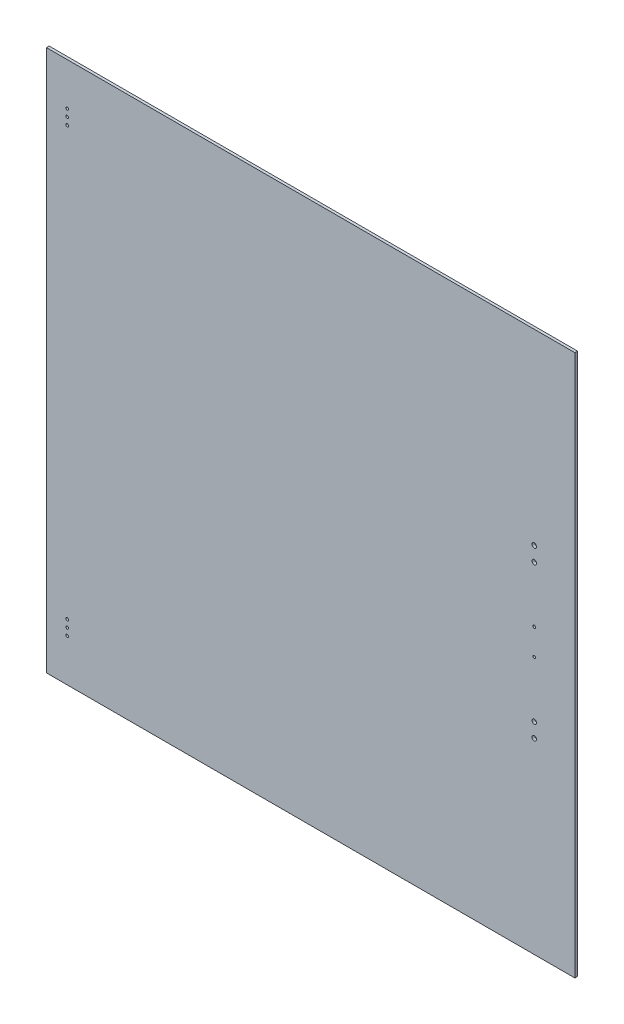
SolidWorks part; units mm, degrees
material "Acrylic (Medium-high impact)"
ref_plane "Front Plane" through (0, 0, 0) normal (0, 0, 1) x (1, 0, 0)
ref_plane "Top Plane" through (0, 0, 0) normal (0, 1, 0) x (1, 0, 0)
ref_plane "Right Plane" through (0, 0, 0) normal (1, 0, 0) x (0, 0, -1)
sketch "Sketch1" plane through (0, 0, 0) normal (0, 0, 1) x (1, 0, 0)
  line L1 (-476.5049, 294.7573) -> (108.9951, 294.7573)
  line L2 (-476.5049, 294.7573) -> (-476.5049, -305.2427)
  line L3 (-476.5049, -305.2427) -> (108.9951, -305.2427)
  line L4 (108.9951, 294.7573) -> (108.9951, -305.2427)
  dimension "D1" = 600
  dimension "D2" = 585.5
extrude "Boss-Extrude1" add sketch "Sketch1" along normal blind 3
sketch "Sketch2" plane through (0, 0, 3) normal (0, 0, 1) x (1, 0, 0)
  line L0 (-476.5049, 294.7573) -> (-476.5049, -305.2427) construction
  line L1 (108.9951, 294.7573) -> (-476.5049, 294.7573) construction
  line L2 (-476.5049, -305.2427) -> (108.9951, -305.2427) construction
  circle A0 centre (-453.5049, 247.7573) radius 1.5
  circle A1 centre (-453.5049, 239.7573) radius 1.5
  circle A2 centre (-453.5049, 231.7573) radius 1.5
  circle A3 centre (-453.5049, -242.2427) radius 1.5
  circle A4 centre (-453.5049, -250.2427) radius 1.5
  circle A5 centre (-453.5049, -258.2427) radius 1.5
  dimension "D1" = 3
  dimension "D4" = 8
  dimension "D5" = 23
  dimension "D6" = 8
  dimension "D7" = 23
  dimension "D8" = 3
  dimension "D11" = 47
  dimension "D12" = 23
  dimension "D2" = 23
  dimension "D3" = 47
  dimension "D9" = 8
  dimension "D10" = 8
extrude "Cut-Extrude1" cut sketch "Sketch2" against normal through all
sketch "Sketch3" plane through (0, 0, 3) normal (0, 0, 1) x (1, 0, 0)
  line L0 (-476.5049, -5.2427) -> (108.9951, -5.2427) construction
  line L1 (-476.5049, 294.7573) -> (-476.5049, -305.2427) construction
  line L2 (108.9951, -305.2427) -> (108.9951, 294.7573) construction
  line L3 (63.9951, 294.7573) -> (63.9951, -305.2427) construction
  line L4 (108.9951, 294.7573) -> (-476.5049, 294.7573) construction
  line L5 (-476.5049, -305.2427) -> (108.9951, -305.2427) construction
  circle A0 centre (63.9951, 87.2573) radius 2.5
  circle A1 centre (63.9951, 71.2573) radius 2.5
  circle A2 centre (63.9951, -81.7427) radius 2.5
  circle A3 centre (63.9951, -97.7427) radius 2.5
  circle A4 centre (63.9951, 9.2573) radius 1.5
  circle A5 centre (63.9951, -19.7427) radius 1.5
  dimension "D1" = 5
  dimension "D2" = 5
  dimension "D3" = 16
  dimension "D4" = 5
  dimension "D5" = 5
  dimension "D6" = 16
  dimension "D7" = 185
  dimension "D8" = 92.5
  dimension "D9" = 45
  dimension "D10" = 45
  dimension "D11" = 45
  dimension "D12" = 45
  dimension "D13" = 3
  dimension "D14" = 3
  dimension "D15" = 29
  dimension "D16" = 14.5
extrude "Cut-Extrude2" cut sketch "Sketch3" against normal through all
